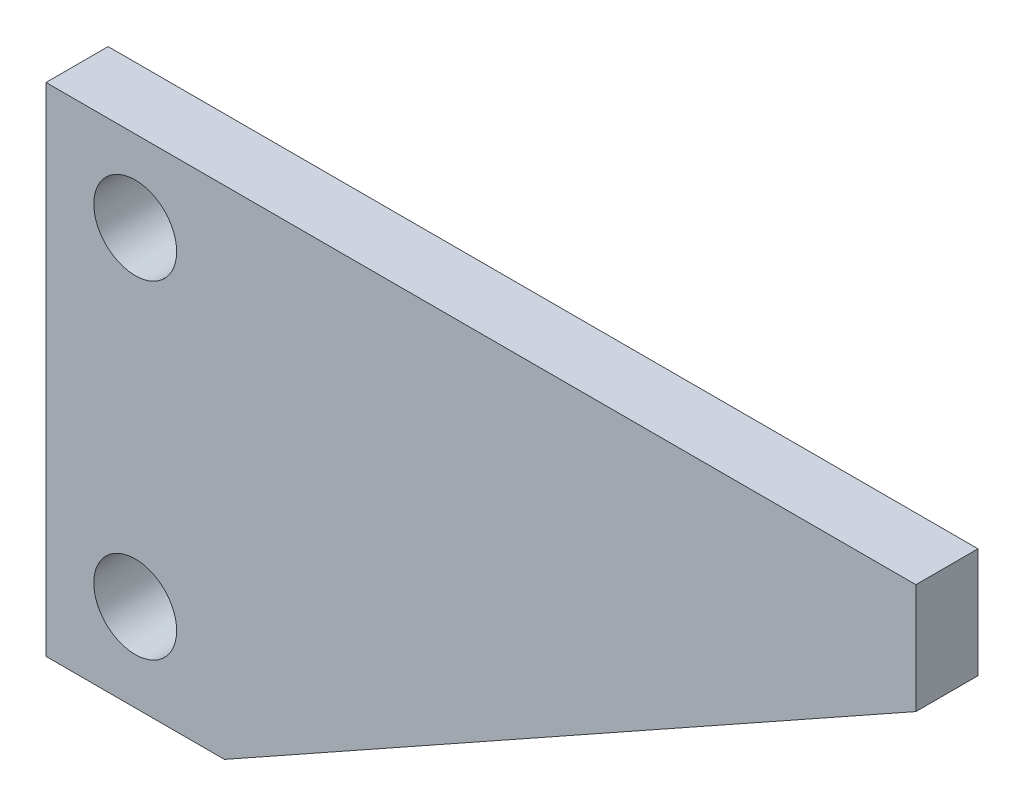
SolidWorks part; units mm, degrees
ref_plane "Front Plane" through (0, 0, 0) normal (0, 0, 1) x (1, 0, 0)
ref_plane "Top Plane" through (0, 0, 0) normal (0, 1, 0) x (1, 0, 0)
ref_plane "Right Plane" through (0, 0, 0) normal (1, 0, 0) x (0, 0, -1)
sketch "Sketch1" plane through (0, 0, 0) normal (0, 0, 1) x (1, 0, 0)
  line L0 (-65.4538, 40.0538) -> (-65.4538, -61.5462)
  line L1 (-65.4538, -61.5462) -> (-28.9821, -61.5462)
  line L2 (-28.9821, -61.5462) -> (112.3462, 17.5846)
  line L3 (112.3462, 17.5846) -> (112.3462, 40.0538)
  line L4 (112.3462, 40.0538) -> (-65.4538, 40.0538)
  circle A0 centre (-47.2179, 23.4462) radius 8.4667
  circle A1 centre (-47.2179, -43.6359) radius 8.4667
  point P9 (-47.2179, -43.6359)
  dimension "D1" = 101.6
  dimension "D2" = 177.8
extrude "Boss-Extrude1" add sketch "Sketch1" along normal blind 12.7
